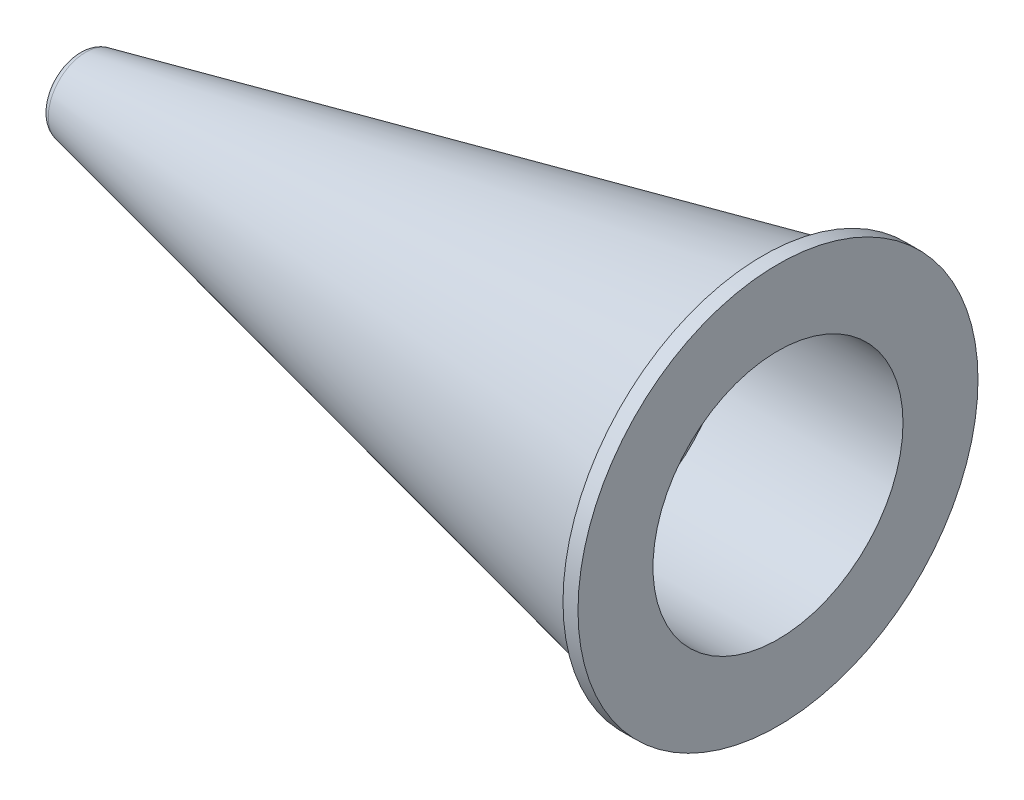
SolidWorks part; units mm, degrees
material "1023 碳钢板 (SS)"
ref_plane "前视基准面" through (0, 0, 0) normal (0, 0, 1) x (1, 0, 0)
ref_plane "上视基准面" through (0, 0, 0) normal (0, 1, 0) x (1, 0, 0)
ref_plane "右视基准面" through (0, 0, 0) normal (1, 0, 0) x (0, 0, -1)
sketch "草图1" plane through (0, 0, 0) normal (0, 0, 1) x (1, 0, 0)
  line L0 (0, 0) -> (0, 4)
  line L1 (0, 4) -> (-0.3, 4)
  line L3 (-15, 0.5) -> (-15, 0)
  line L4 (-15, 0) -> (0, 0)
  line L5 (-0.3, 4) -> (-0.3, 3.7)
  line L6 (-0.3, 3.7) -> (-15, 0.5)
  dimension "D1" = 4
  dimension "D2" = 0.5
  dimension "D3" = 0.3
  dimension "D4" = 15
  dimension "D5" = 0.3
revolve "旋转1" add sketch "草图1" angle 360 about L4
sketch "草图2" plane through (0, 0, 0) normal (1, 0, 0) x (0, 0, -1)
  circle A0 centre (0, 0) radius 2.5
  dimension "D1" = 5
extrude "切除-拉伸1" cut sketch "草图2" against normal blind 3.5
sketch "草图3" plane through (-15, 0, 0) normal (-1, 0, 0) x (0, 0, 1)
  circle A0 centre (0, 0) radius 1.5
  dimension "D1" = 3
extrude "切除-拉伸2" cut sketch "草图3" against normal blind 1
fillet "圆角1" radius 0.2 1 edges at (-14, 0, 0.7177)
sketch "草图4" plane through (-14, 0, 0) normal (-1, 0, 0) x (0, 0, 1)
  circle A0 centre (0, 0) radius 0.05
  dimension "D1" = 0.1
extrude "凸台-拉伸1" add sketch "草图4" along normal blind 0.05
sketch "草图5" plane through (0, 0, 0) normal (0, 1, 0) x (1, 0, 0)
  line L0 (-14, -0.05) -> (-14.05, -0.03)
  line L1 (-14.05, 0.05) -> (-14.05, -0.05) construction
  line L2 (-14.05, 0) -> (-14, 0) construction
  line L3 (-14, 0.05) -> (-14, -0.05) construction
  line L4 (-14, -0.05) -> (-14.05, -0.05)
  line L5 (-14.05, -0.05) -> (-14.05, -0.03)
  dimension "D1" = 0.02
revolve "切除-旋转1" cut sketch "草图5" angle 360 about L2
